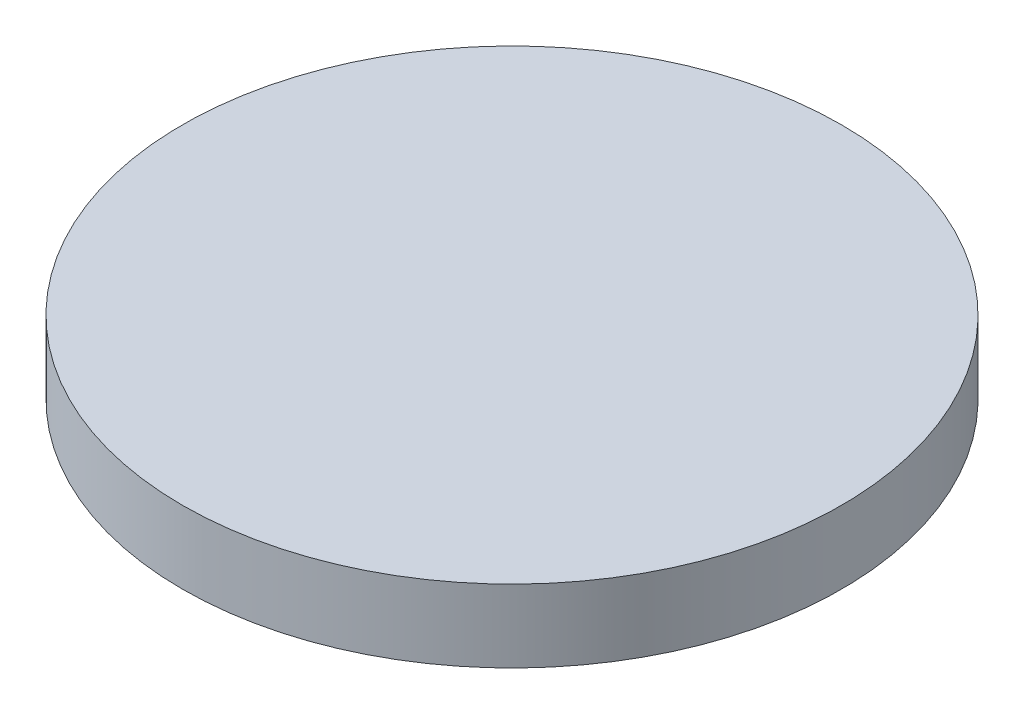
SolidWorks part; units mm, degrees
material "1.8550 (34CrAlNi7-10)"
ref_plane "Front Plane" through (0, 0, 0) normal (0, 0, 1) x (1, 0, 0)
ref_plane "Top Plane" through (0, 0, 0) normal (0, 1, 0) x (1, 0, 0)
ref_plane "Right Plane" through (0, 0, 0) normal (1, 0, 0) x (0, 0, -1)
sketch "Sketch1" plane through (0, 0, 0) normal (0, 1, 0) x (1, 0, 0)
  line L0 (0, 0) -> (15.875, 0) construction
  circle A0 centre (0, 0) radius 15.875
extrude "Boss-Extrude1" add sketch "Sketch1" along normal blind 3.5
